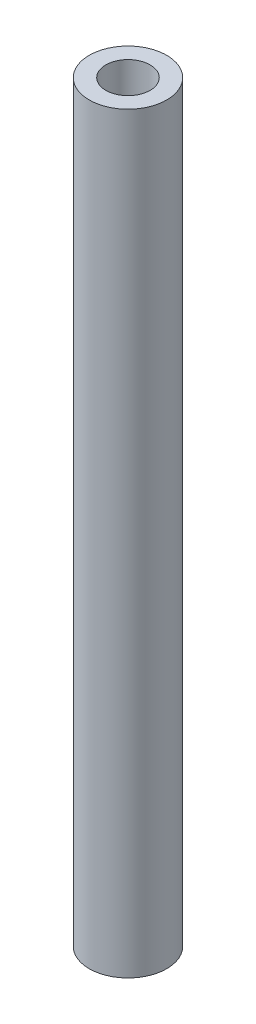
SolidWorks part; units mm, degrees
ref_plane "前视" through (0, 0, 0) normal (0, 0, 1) x (1, 0, 0)
ref_plane "上视" through (0, 0, 0) normal (0, 1, 0) x (1, 0, 0)
ref_plane "右视" through (0, 0, 0) normal (1, 0, 0) x (0, 0, -1)
sketch "草图1" plane through (0, 0, 0) normal (0, 1, 0) x (1, 0, 0)
  circle A0 centre (0, 0) radius 4
  circle A1 centre (0, 0) radius 7
  dimension "D1" = 8
  dimension "D2" = 14
extrude "凸台-拉伸1" add sketch "草图1" along normal blind 136
